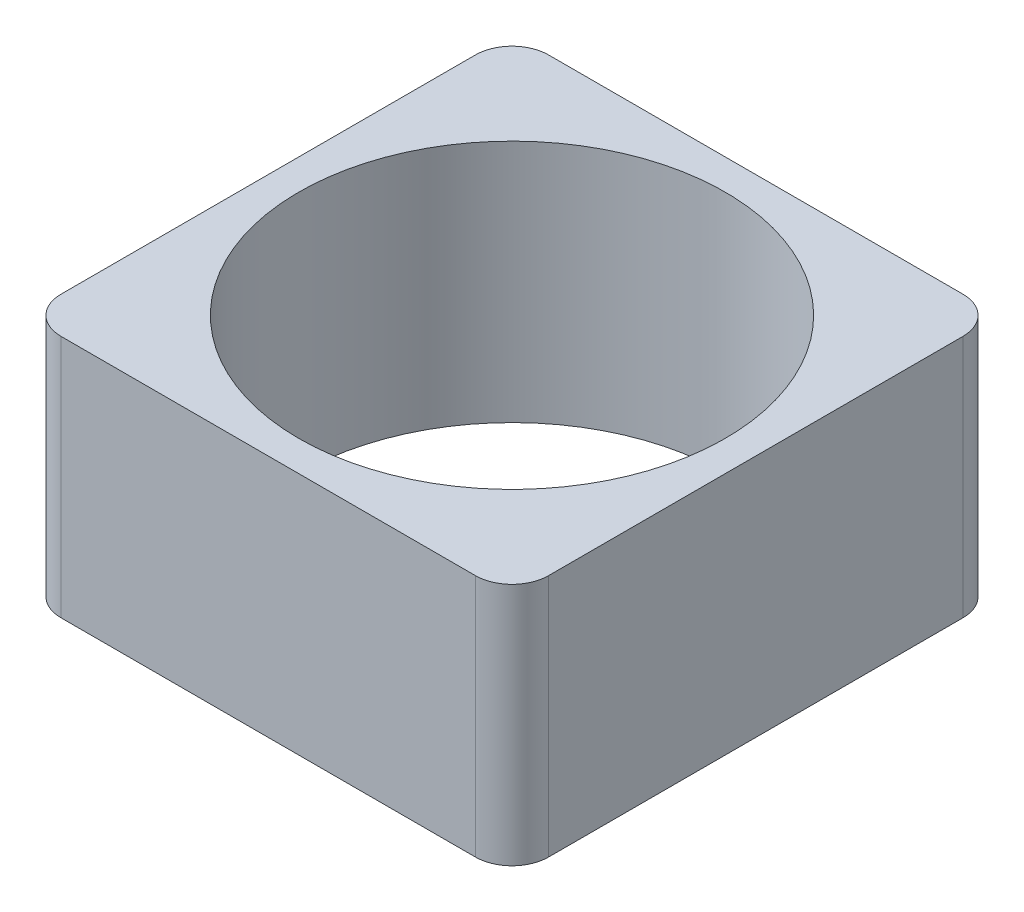
SolidWorks part; units mm, degrees
ref_plane "Front" through (0, 0, 0) normal (0, 0, 1) x (1, 0, 0)
ref_plane "Top" through (0, 0, 0) normal (0, 1, 0) x (1, 0, 0)
ref_plane "Right" through (0, 0, 0) normal (1, 0, 0) x (0, 0, -1)
sketch "Sketch1" plane through (0, 0, 0) normal (0, 1, 0) x (1, 0, 0)
  line L1 (-20, -20) -> (20, -20)
  line L2 (-20, -20) -> (-20, 20)
  line L3 (-20, 20) -> (20, 20)
  line L4 (20, -20) -> (20, 20)
  line L5 (-20, -20) -> (20, 20) construction
  line L6 (-20, 20) -> (20, -20) construction
  point P0 (0, 0)
  point P6 (20, 20)
  dimension "D1" = 40
extrude "Boss-Extrude1" add sketch "Sketch1" along normal blind 20
fillet "Fillet1" radius 3 4 edges at (-20, 10, -20) (-20, 10, 20) (20, 10, -20) (20, 10, 20)
sketch "Sketch2" plane through (0, 20, 0) normal (0, 1, 0) x (1, 0, 0)
  circle A0 centre (0, 0) radius 17.5
  dimension "D1" = 35
extrude "Cut-Extrude1" cut sketch "Sketch2" against normal through all
